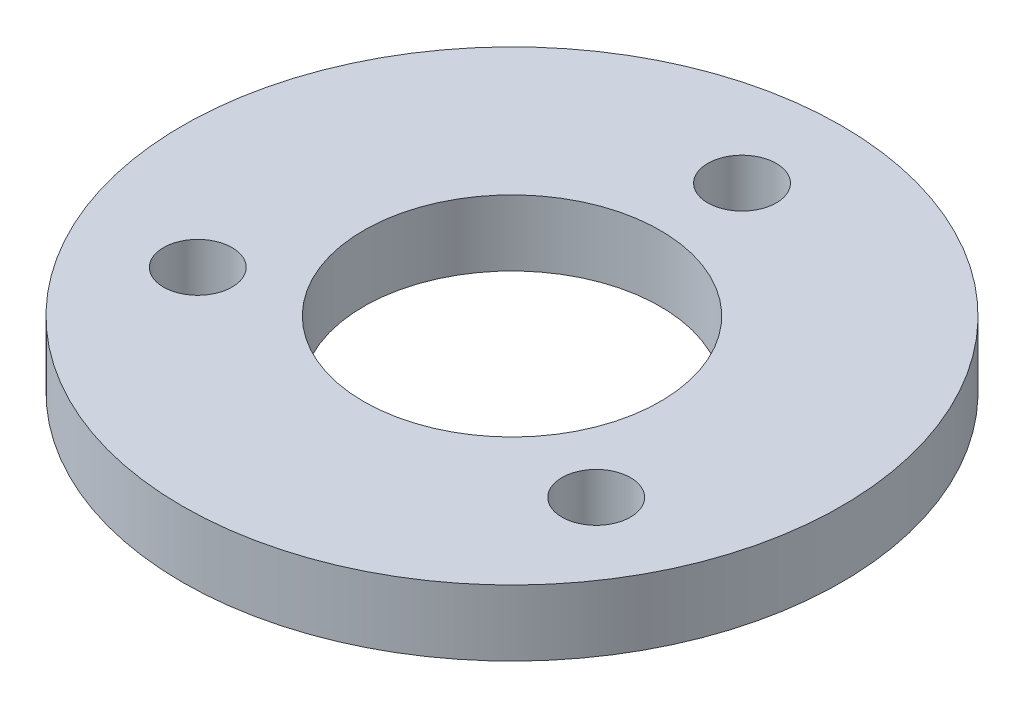
SolidWorks part; units mm, degrees
ref_plane "前视基准面" through (0, 0, 0) normal (0, 0, 1) x (1, 0, 0)
ref_plane "上视基准面" through (0, 0, 0) normal (0, 1, 0) x (1, 0, 0)
ref_plane "右视基准面" through (0, 0, 0) normal (1, 0, 0) x (0, 0, -1)
sketch "草图1" plane through (0, 0, 0) normal (0, 1, 0) x (1, 0, 0)
  line L0 (0, 17.45) -> (0, 0) construction
  line L1 (0, 0) -> (-30.963, 0) construction
  circle A0 centre (0, 0) radius 25
  circle A1 centre (0, 17.45) radius 2.6
  circle A2 centre (15.1121, -8.725) radius 2.6
  circle A3 centre (-15.1121, -8.725) radius 2.6
  circle A5 centre (0, 0) radius 11.25
  point P16 (0, 0)
  dimension "D1" = 17.45
  dimension "D2" = 50
  dimension "D3" = 5.2
  dimension "D5" = 22.5
  dimension "D4" = 3
extrude "凸台-拉伸1" add sketch "草图1" along normal blind 5
